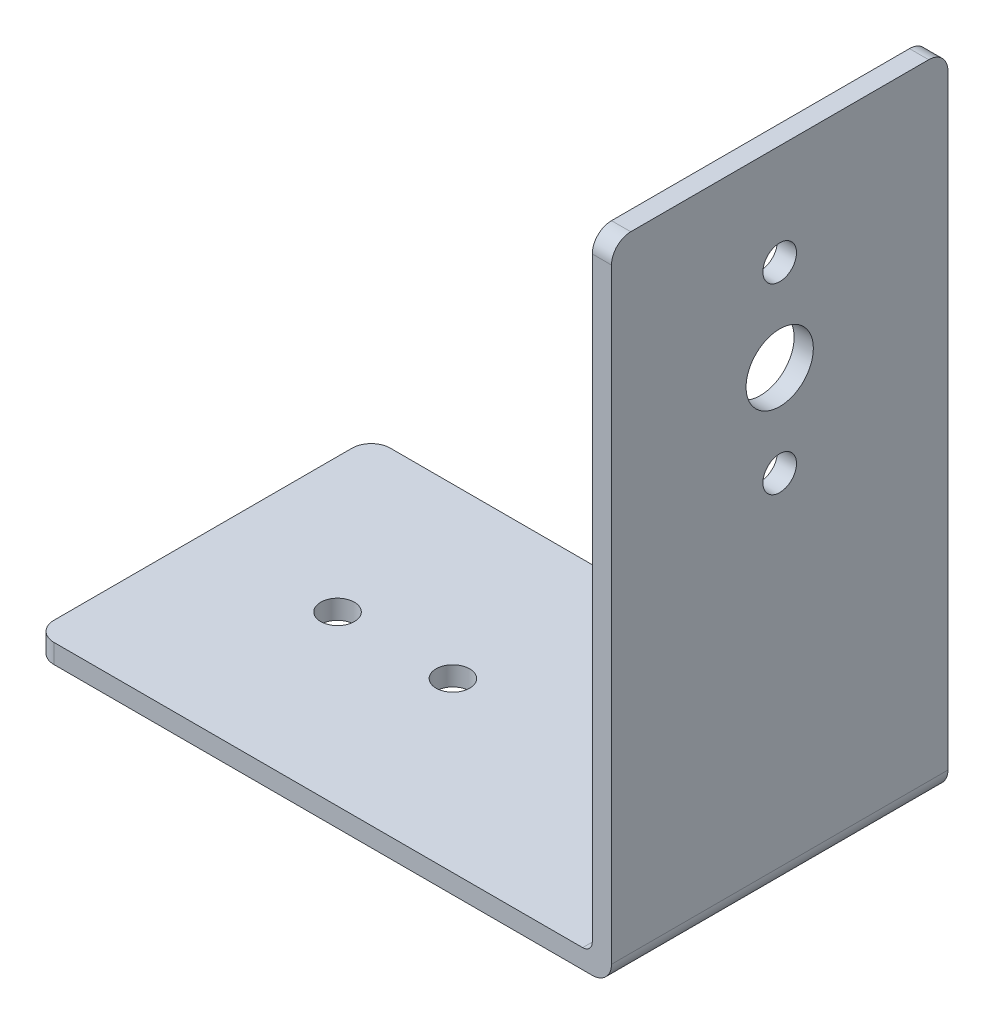
SolidWorks part; units mm, degrees
material "Alliage 2024"
ref_plane "Plan de face" through (0, 0, 0) normal (0, 0, 1) x (1, 0, 0)
ref_plane "Plan de dessus" through (0, 0, 0) normal (0, 1, 0) x (1, 0, 0)
ref_plane "Plan de droite" through (0, 0, 0) normal (1, 0, 0) x (0, 0, -1)
sketch "Esquisse1" plane through (0, 0, 0) normal (0, 0, 1) x (1, 0, 0)
  line L0 (0, 0) -> (58, 0)
  line L1 (58, 0) -> (58, 65)
  dimension "D1" = 0
  dimension "D3" = 58
  dimension "D4" = 65
extrude "Extru.-Mince1" add sketch "Esquisse1" along normal blind 35 thin contours L0 L1
fillet "Congé1" radius 2 1 edges at (60, -2, 17.5)
fillet "Congé3" radius 1 1 edges at (58, 0, 17.5)
sketch "Esquisse3" plane through (60, 0, 0) normal (1, 0, 0) x (0, 0, -1)
  line L0 (-17.5, 34.095) -> (-17.5, 61.4768) construction
  line L1 (-30.3181, 45) -> (10.1, 45) construction
  line L2 (-35, 0) -> (-35, 65) construction
  line L3 (-35, 65) -> (0, 65) construction
  circle A0 centre (-17.5, 35.5) radius 1.75
  circle A1 centre (-17.5, 54.5) radius 1.75
  circle A4 centre (-17.5, 45) radius 3.5
  dimension "D2" = 20
  dimension "D3" = 9.5
  dimension "D4" = 9.5
  dimension "D5" = 3.5
  dimension "D8" = 3.5
  dimension "D11" = 7
  dimension "D1" = 17.5
extrude "Enlèv. mat.-Extru.2" cut sketch "Esquisse3" against normal blind 2
fillet "Congé5" radius 2 1 edges at (59, 65, 35)
fillet "Congé6" radius 2 1 edges at (59, 65, 0)
fillet "Congé7" radius 2 1 edges at (0, -1, 0)
fillet "Congé8" radius 2 1 edges at (0, -1, 35)
sketch "Esquisse4" plane through (0, 0, 0) normal (0, 1, 0) x (1, 0, 0)
  line L0 (20, 6.8371) -> (20, -34.2545) construction
  line L1 (29.5005, -17.5) -> (81.1492, -17.5) construction
  line L2 (2, 0) -> (57, 0) construction
  line L3 (60, -33) -> (60, -2) construction
  circle A2 centre (26, -17.5) radius 1.75
  circle A3 centre (14, -17.5) radius 1.75
  dimension "D3" = 3.5
  dimension "D6" = 3.5
  dimension "D1" = 17.5
  dimension "D2" = 6
  dimension "D9" = 40
  dimension "D10" = 6
extrude "Enlèv. mat.-Extru.3" cut sketch "Esquisse4" against normal blind 2
